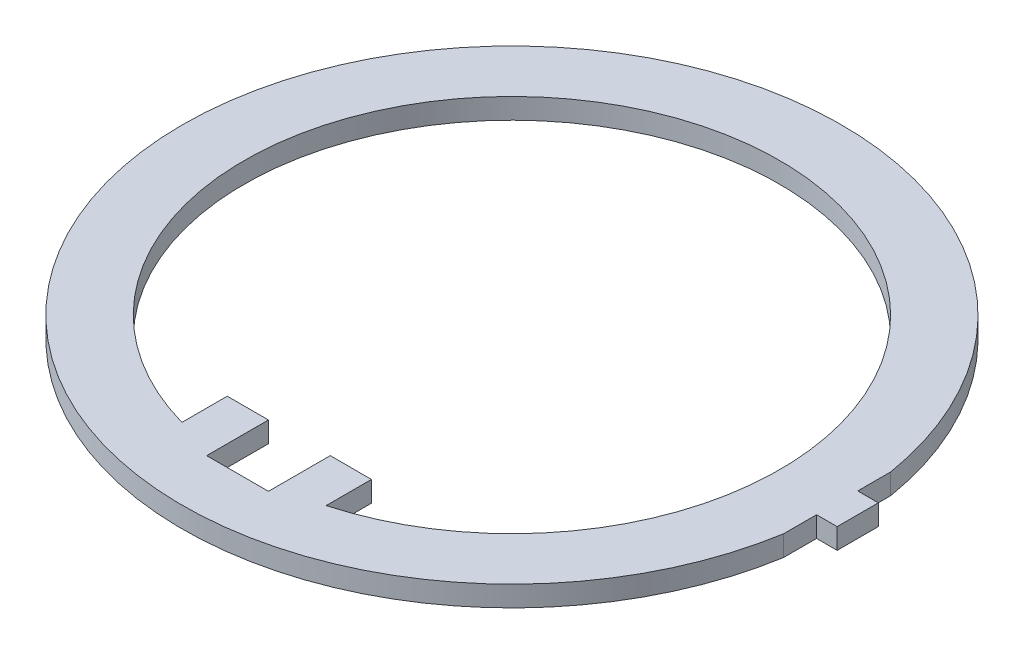
SolidWorks part; units mm, degrees
ref_plane "Front Plane" through (0, 0, 0) normal (0, 0, 1) x (1, 0, 0)
ref_plane "Top Plane" through (0, 0, 0) normal (0, 1, 0) x (1, 0, 0)
ref_plane "Right Plane" through (0, 0, 0) normal (1, 0, 0) x (0, 0, -1)
sketch "Sketch1" plane through (0, 0, 0) normal (0, 1, 0) x (1, 0, 0)
  line L0 (0, 0) -> (19.05, 0)
  line L1 (19.05, 0) -> (19.05, 19.05)
  line L2 (19.05, 19.05) -> (31.75, 19.05)
  line L3 (31.75, 19.05) -> (31.75, 5.08)
  line L4 (0, 0) -> (0, 19.05)
  line L5 (0, 19.05) -> (-12.7, 19.05)
  line L6 (-12.7, 19.05) -> (-12.7, 5.08)
  line L7 (109.7746, 101.0919) -> (109.7746, 90.9319)
  line L8 (109.7746, 90.9319) -> (116.1246, 90.9319)
  line L9 (116.1246, 90.9319) -> (116.1246, 78.2319)
  line L10 (116.1246, 78.2319) -> (109.7746, 78.2319)
  line L11 (109.7746, 78.2319) -> (109.7746, 68.0719)
  arc A0 (-12.7, 5.08) -> (31.75, 5.08) centre (9.525, 84.5819) cw
  arc A1 (109.7746, 101.0919) -> (109.7746, 68.0719) centre (9.525, 84.5819) ccw
  point P17 (0, 0)
  dimension "D3" = 82.55
  dimension "D7" = 101.6
  dimension "D1" = 12.7
  dimension "D2" = 6.35
  dimension "D4" = 19.05
  dimension "D5" = 12.7
  dimension "D6" = 19.05
  dimension "D8" = 13.97
  dimension "D9" = 10.16
extrude "Boss-Extrude1" add sketch "Sketch1" along normal blind 6.35
